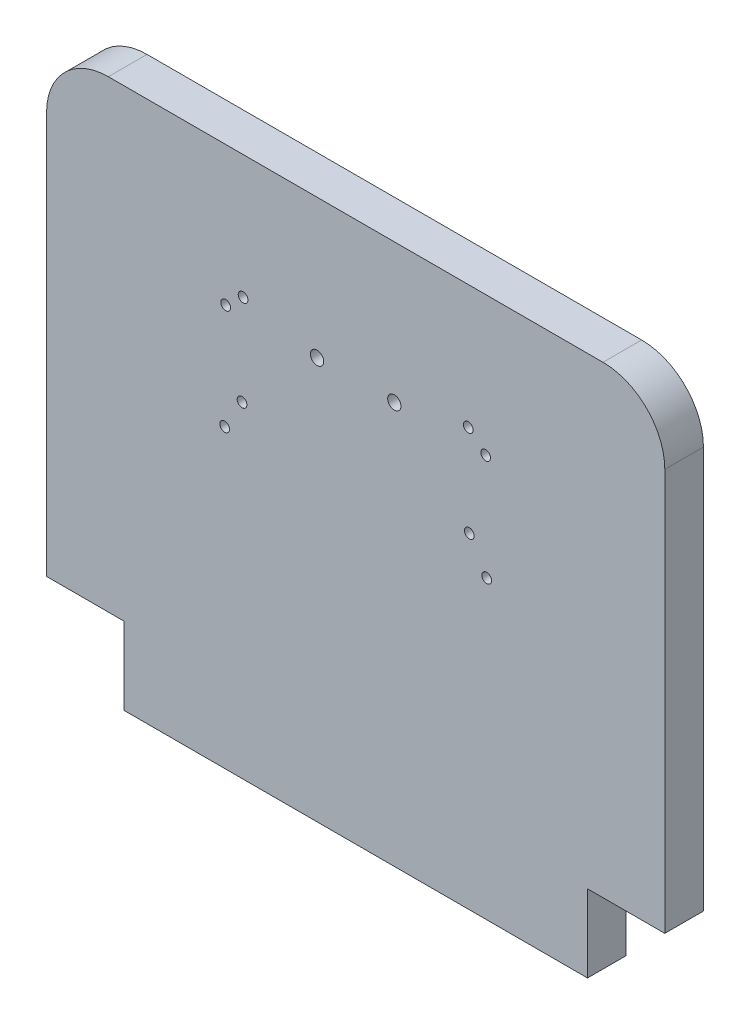
SolidWorks part; units mm, degrees
ref_plane "Front Plane" through (0, 0, 0) normal (0, 0, 1) x (1, 0, 0)
ref_plane "Top Plane" through (0, 0, 0) normal (0, 1, 0) x (1, 0, 0)
ref_plane "Right Plane" through (0, 0, 0) normal (1, 0, 0) x (0, 0, -1)
sketch "Sketch1" plane through (0, 0, 0) normal (0, 0, 1) x (1, 0, 0)
  line L0 (88.9, 0) -> (101.6, 0)
  line L1 (0, 0) -> (12.7, 0)
  line L2 (0, 0) -> (0, 76.2)
  line L3 (0, 76.2) -> (101.6, 76.2)
  line L4 (101.6, 0) -> (101.6, 76.2)
  line L6 (12.7, 0) -> (12.7, -12.7)
  line L7 (12.7, -12.7) -> (88.9, -12.7)
  line L8 (88.9, 0) -> (88.9, -12.7)
  circle A0 centre (44.45, 53.34) radius 1.0922
  circle A1 centre (57.15, 53.34) radius 1.0922
  circle A2 centre (32.3, 55.88) radius 0.8
  circle A3 centre (69.3, 55.88) radius 0.8
  circle A4 centre (32.1253, 40.88) radius 0.8
  circle A6 centre (69.4747, 40.88) radius 0.8
  circle A13 centre (29.4386, 53.34) radius 0.8
  circle A14 centre (29.2639, 35.954) radius 0.8
  circle A15 centre (72.3361, 35.954) radius 0.8
  circle A16 centre (72.1614, 53.34) radius 0.8
  dimension "D1" = 76.2
  dimension "D2" = 101.6
  dimension "D3" = 12.7
  dimension "D4" = 76.2
  dimension "D5" = 12.7
  dimension "D7" = 66.04
  dimension "D9" = 15
  dimension "D12" = 68.58
  dimension "D13" = 17.386
  dimension "D15" = 66.04
extrude "Boss-Extrude1" add sketch "Sketch1" along normal blind 6.35
fillet "Fillet1" radius 10.16 2 edges at (101.6, 76.2, 3.175) (0, 76.2, 3.175)
